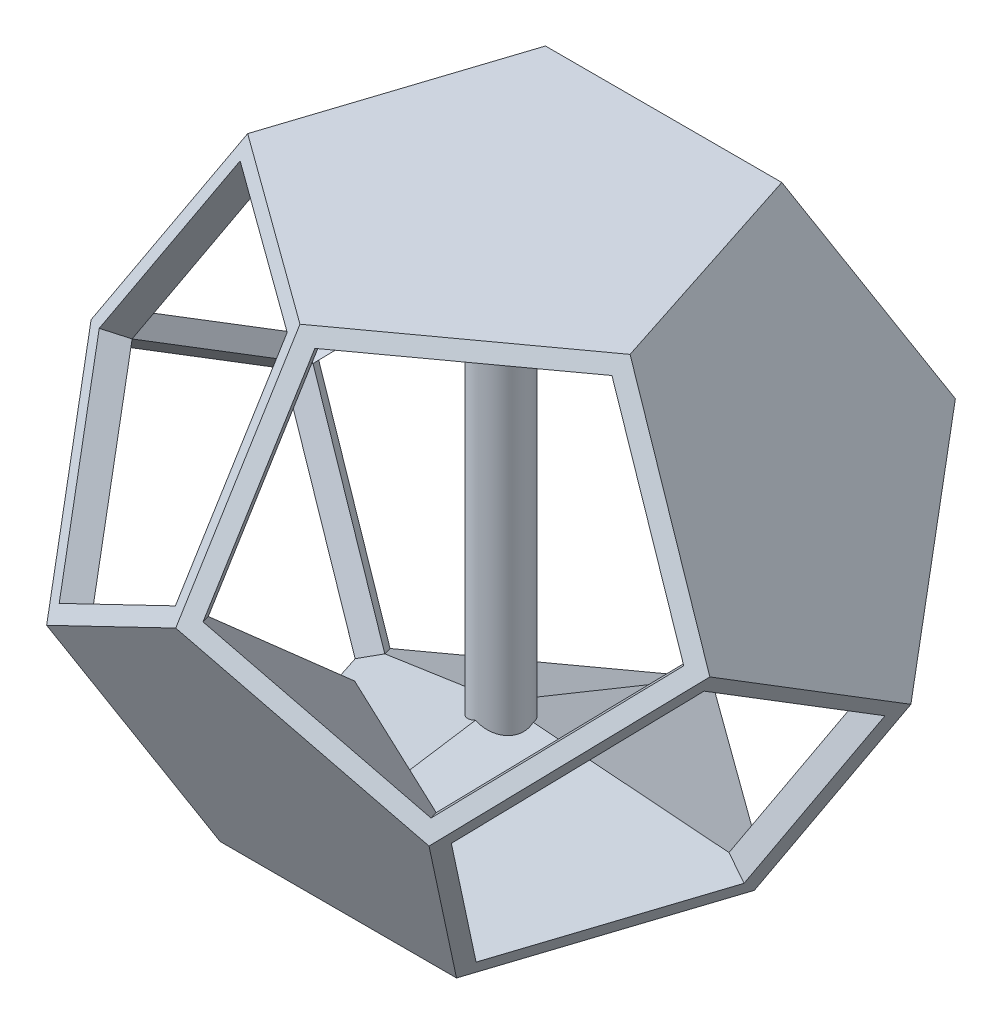
SolidWorks part; units mm, degrees
ref_plane "Front Plane" through (0, 0, 0) normal (0, 0, 1) x (1, 0, 0)
ref_plane "Top Plane" through (0, 0, 0) normal (0, 1, 0) x (1, 0, 0)
ref_plane "Right Plane" through (0, 0, 0) normal (1, 0, 0) x (0, 0, -1)
sketch "Sketch1" plane through (0, 0, 0) normal (0, 1, 0) x (1, 0, 0)
  line L6 (0, 50) -> (-47.5528, 15.4508)
  line L7 (-47.5528, 15.4508) -> (-29.3893, -40.4508)
  line L8 (-29.3893, -40.4508) -> (29.3893, -40.4508)
  line L9 (29.3893, -40.4508) -> (47.5528, 15.4508)
  line L10 (47.5528, 15.4508) -> (0, 50)
  circle A0 centre (0, 0) radius 50 construction
  dimension "D1" = 100
extrude "creation_extrude" add sketch "Sketch1" along normal blind 130.9017 draft 26.565 contours L6 L7 L8 L9 L10
sketch "Sketch2" plane through (0, 130.9017, 0) normal (0, 1, 0) x (1, 0, 0)
  line L1 (0, -50) -> (47.5528, -15.4508)
  line L2 (47.5528, -15.4508) -> (29.3893, 40.4508)
  line L3 (29.3893, 40.4508) -> (-29.3893, 40.4508)
  line L4 (-29.3893, 40.4508) -> (-47.5528, -15.4508)
  line L5 (-47.5528, -15.4508) -> (0, -50)
  circle A0 centre (0, 0) radius 50 construction
  dimension "D1" = 100
extrude "creation_cut" cut sketch "Sketch2" against normal blind 130.9017 draft 26.565 flip side to cut
sketch "Sketch3" plane through (0, 130.9017, 0) normal (0, 1, 0) x (1, 0, 0)
  line L1 (0, -45) -> (42.7975, -13.9058)
  line L2 (42.7975, -13.9058) -> (26.4503, 36.4058)
  line L3 (26.4503, 36.4058) -> (-26.4503, 36.4058)
  line L4 (-26.4503, 36.4058) -> (-42.7975, -13.9058)
  line L5 (-42.7975, -13.9058) -> (0, -45)
  circle A0 centre (0, 0) radius 45 construction
  dimension "D1" = 90
extrude "A" [suppressed] cut sketch "Sketch3" against normal blind 25.4
sketch "Sketch4" plane through (0, 0, 0) normal (0, -1, 0) x (1, 0, 0)
  line L1 (0, -45) -> (42.7975, -13.9058)
  line L2 (42.7975, -13.9058) -> (26.4503, 36.4058)
  line L3 (26.4503, 36.4058) -> (-26.4503, 36.4058)
  line L4 (-26.4503, 36.4058) -> (-42.7975, -13.9058)
  line L5 (-42.7975, -13.9058) -> (0, -45)
  circle A0 centre (0, 0) radius 45 construction
  dimension "D1" = 90
extrude "A_inv" [suppressed] cut sketch "Sketch4" against normal blind 25.4
sketch "Sketch5" plane through (0, 42.3607, -84.7214) normal (0, 0.4472, -0.8944) x (-1, 0, 0)
  line L0 (0, 58.541) -> (-47.5528, 43.0902) construction
  line L2 (-42.7975, 44.6353) -> (0, 13.541)
  line L3 (0, 13.541) -> (42.7975, 44.6353)
  line L4 (42.7975, 44.6353) -> (26.4503, 94.9468)
  line L5 (26.4503, 94.9468) -> (-26.4503, 94.9468)
  line L6 (-26.4503, 94.9468) -> (-42.7975, 44.6353)
  circle A0 centre (0, 58.541) radius 50 construction
  circle A1 centre (0, 58.541) radius 45 construction
  dimension "D1" = 90
extrude "B" cut sketch "Sketch5" against normal blind 50.8
sketch "Sketch6" plane through (0, -16.1803, 32.3607) normal (0, -0.4472, 0.8944) x (1, 0, 0)
  line L0 (0, 58.541) -> (-47.5528, 73.9919) construction
  line L2 (-42.7975, 72.4468) -> (-26.4503, 22.1353)
  line L3 (-26.4503, 22.1353) -> (26.4503, 22.1353)
  line L4 (26.4503, 22.1353) -> (42.7975, 72.4468)
  line L5 (42.7975, 72.4468) -> (0, 103.541)
  line L6 (0, 103.541) -> (-42.7975, 72.4468)
  circle A0 centre (0, 58.541) radius 50 construction
  circle A1 centre (0, 58.541) radius 45 construction
  dimension "D1" = 90
extrude "B_inv" [suppressed] cut sketch "Sketch6" against normal blind 25.4
sketch "Sketch7" plane through (80.5748, 42.3607, -26.1803) normal (0.8507, 0.4472, -0.2764) x (-0.2446, -0.1286, -0.961)
  line L0 (-8.4181, 57.9326) -> (40.8623, 49.4804) construction
  line L2 (35.9343, 50.3256) -> (12.5223, 97.7635)
  line L3 (12.5223, 97.7635) -> (-39.8286, 90.1565)
  line L4 (-39.8286, 90.1565) -> (-48.7712, 38.0171)
  line L5 (-48.7712, 38.0171) -> (-1.9472, 13.4003)
  line L6 (-1.9472, 13.4003) -> (35.9343, 50.3256)
  circle A0 centre (-8.4181, 57.9326) radius 50 construction
  circle A1 centre (-8.4181, 57.9326) radius 45 construction
  dimension "D1" = 90
extrude "C" [suppressed] cut sketch "Sketch7" against normal blind 25.4
sketch "Sketch8" plane through (-30.7768, -16.1803, 10) normal (-0.8507, -0.4472, 0.2764) x (0.2446, 0.1286, 0.961)
  line L0 (8.4181, 57.9326) -> (-36.4187, 80.0609) construction
  line L2 (-31.935, 77.8481) -> (-22.9924, 25.7087)
  line L3 (-22.9924, 25.7087) -> (29.3585, 18.1017)
  line L4 (29.3585, 18.1017) -> (52.7705, 65.5396)
  line L5 (52.7705, 65.5396) -> (14.889, 102.4649)
  line L6 (14.889, 102.4649) -> (-31.935, 77.8481)
  circle A0 centre (8.4181, 57.9326) radius 50 construction
  circle A1 centre (8.4181, 57.9326) radius 45 construction
  dimension "D1" = 90
extrude "C_inv" cut sketch "Sketch8" against normal blind 50.8
sketch "Sketch9" plane through (49.798, 42.3607, 68.541) normal (0.5257, 0.4472, 0.7236) x (0.8507, -0.2764, -0.4472)
  line L0 (-18.0902, 55.6758) -> (-2.6393, 103.2286) construction
  line L2 (-4.1844, 98.4734) -> (-54.4959, 82.1262)
  line L3 (-54.4959, 82.1262) -> (-54.4959, 29.2255)
  line L4 (-54.4959, 29.2255) -> (-4.1844, 12.8783)
  line L5 (-4.1844, 12.8783) -> (26.9098, 55.6758)
  line L6 (26.9098, 55.6758) -> (-4.1844, 98.4734)
  circle A0 centre (-18.0902, 55.6758) radius 50 construction
  circle A1 centre (-18.0902, 55.6758) radius 45 construction
  dimension "D1" = 90
extrude "D" cut sketch "Sketch9" against normal blind 50.8
sketch "Sketch10" plane through (-19.0211, -16.1803, -26.1803) normal (-0.5257, -0.4472, -0.7236) x (-0.8507, 0.2764, 0.4472)
  line L0 (18.0902, 55.6758) -> (33.541, 103.2286) construction
  line L2 (31.9959, 98.4734) -> (-18.3156, 82.1262)
  line L3 (-18.3156, 82.1262) -> (-18.3156, 29.2255)
  line L4 (-18.3156, 29.2255) -> (31.9959, 12.8783)
  line L5 (31.9959, 12.8783) -> (63.0902, 55.6758)
  line L6 (63.0902, 55.6758) -> (31.9959, 98.4734)
  circle A0 centre (18.0902, 55.6758) radius 50 construction
  circle A1 centre (18.0902, 55.6758) radius 45 construction
  dimension "D1" = 90
extrude "D_inv" cut sketch "Sketch10" against normal blind 50.8
sketch "Sketch11" plane through (-49.798, 42.3607, 68.541) normal (-0.5257, 0.4472, 0.7236) x (0.8507, 0.2764, 0.4472)
  line L0 (18.0902, 55.6758) -> (2.6393, 103.2286) construction
  line L2 (4.1844, 98.4734) -> (-26.9098, 55.6758)
  line L3 (-26.9098, 55.6758) -> (4.1844, 12.8783)
  line L4 (4.1844, 12.8783) -> (54.4959, 29.2255)
  line L5 (54.4959, 29.2255) -> (54.4959, 82.1262)
  line L6 (54.4959, 82.1262) -> (4.1844, 98.4734)
  circle A0 centre (18.0902, 55.6758) radius 50 construction
  circle A1 centre (18.0902, 55.6758) radius 45 construction
  dimension "D1" = 90
extrude "E" cut sketch "Sketch11" against normal blind 50.8
sketch "Sketch12" plane through (19.0211, -16.1803, -26.1803) normal (0.5257, -0.4472, -0.7236) x (-0.8507, -0.2764, -0.4472)
  line L0 (-18.0902, 55.6758) -> (-33.541, 103.2286) construction
  line L2 (-31.9959, 98.4734) -> (-63.0902, 55.6758)
  line L3 (-63.0902, 55.6758) -> (-31.9959, 12.8783)
  line L4 (-31.9959, 12.8783) -> (18.3156, 29.2255)
  line L5 (18.3156, 29.2255) -> (18.3156, 82.1262)
  line L6 (18.3156, 82.1262) -> (-31.9959, 98.4734)
  circle A0 centre (-18.0902, 55.6758) radius 50 construction
  circle A1 centre (-18.0902, 55.6758) radius 45 construction
  dimension "D1" = 90
extrude "E_inv" cut sketch "Sketch12" against normal blind 50.8
sketch "Sketch13" plane through (-80.5748, 42.3607, -26.1803) normal (-0.8507, 0.4472, -0.2764) x (-0.2446, 0.1286, 0.961)
  line L0 (8.4181, 57.9326) -> (-14.849, 102.1892) construction
  line L2 (-12.5223, 97.7635) -> (-35.9343, 50.3256)
  line L3 (-35.9343, 50.3256) -> (1.9472, 13.4003)
  line L4 (1.9472, 13.4003) -> (48.7712, 38.0171)
  line L5 (48.7712, 38.0171) -> (39.8286, 90.1565)
  line L6 (39.8286, 90.1565) -> (-12.5223, 97.7635)
  circle A0 centre (8.4181, 57.9326) radius 50 construction
  circle A1 centre (8.4181, 57.9326) radius 45 construction
  dimension "D1" = 90
extrude "F" cut sketch "Sketch13" against normal blind 50.8
sketch "Sketch14" plane through (30.7768, -16.1803, 10) normal (0.8507, -0.4472, 0.2764) x (0.2446, -0.1286, -0.961)
  line L0 (-8.4181, 57.9326) -> (-31.6852, 13.676) construction
  line L2 (-29.3585, 18.1017) -> (22.9924, 25.7087)
  line L3 (22.9924, 25.7087) -> (31.935, 77.8481)
  line L4 (31.935, 77.8481) -> (-14.889, 102.4649)
  line L5 (-14.889, 102.4649) -> (-52.7705, 65.5396)
  line L6 (-52.7705, 65.5396) -> (-29.3585, 18.1017)
  circle A0 centre (-8.4181, 57.9326) radius 50 construction
  circle A1 centre (-8.4181, 57.9326) radius 45 construction
  dimension "D1" = 90
extrude "F_inv" cut sketch "Sketch14" against normal blind 50.8
sketch "Sketch17" plane through (0, 130.9017, 0) normal (0, 1, 0) x (1, 0, 0)
  circle A0 centre (0, 0) radius 6.35
  dimension "D1" = 12.7
extrude "Boss-Extrude1" add sketch "Sketch17" against normal blind 127
equation "\"ratio\"= ( sin ( 18 ) + 1 ) 'ratio base:height"
equation "\"height\"= \"base\" * \"ratio\"'height of extrude"
equation "\"D1@Sketch1\" = \"base\""
equation "\"D1@Sketch2\"= \"D1@Sketch1\""
equation "\"D1@creation_cut\"= \"height\""
equation "\"D1@creation_extrude\"= \"height\""
equation "\"base\"= 10cm"
equation "\"D1@Sketch3\" = \"base\" * \"thick\""
equation "\"thick\"= 0.9"
equation "\"D1@Sketch4\"= \"base\" * \"thick\""
equation "\"D1@Sketch5\"= \"base\" * \"thick\""
equation "\"D1@Sketch6\"= \"base\" * \"thick\""
equation "\"D1@Sketch7\"= \"base\" * \"thick\""
equation "\"D1@Sketch8\"= \"base\" * \"thick\""
equation "\"D1@Sketch9\"= \"base\" * \"thick\""
equation "\"D1@Sketch10\"= \"base\" * \"thick\""
equation "\"D1@Sketch11\"= \"base\" * \"thick\""
equation "\"D1@Sketch12\"= \"base\" * \"thick\""
equation "\"D1@Sketch13\"= \"base\" * \"thick\""
equation "\"D1@Sketch14\"= \"base\" * \"thick\""
